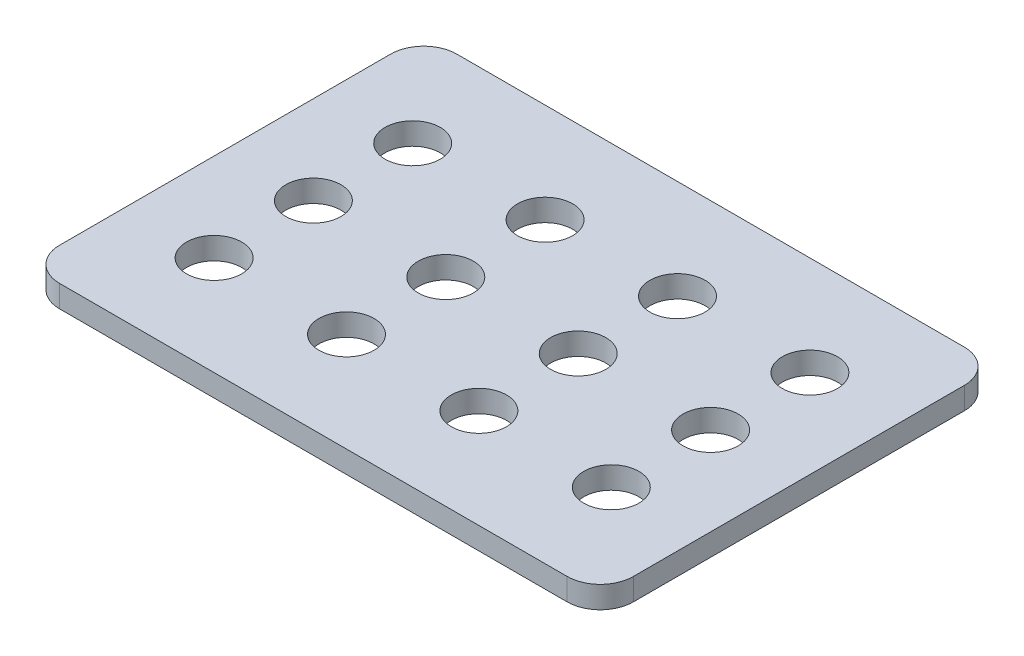
SolidWorks part; units mm, degrees
ref_plane "Front Plane" through (0, 0, 0) normal (0, 0, 1) x (1, 0, 0)
ref_plane "Top Plane" through (0, 0, 0) normal (0, 1, 0) x (1, 0, 0)
ref_plane "Right Plane" through (0, 0, 0) normal (1, 0, 0) x (0, 0, -1)
sketch "Sketch1" plane through (0, 0, 0) normal (0, 1, 0) x (1, 0, 0)
  line L0 (40, 45) -> (0, 45) construction
  line L1 (15, 0) -> (245, 0)
  line L2 (0, 15) -> (0, 165)
  line L3 (15, 180) -> (245, 180)
  line L4 (260, 15) -> (260, 165)
  line L5 (220, 45) -> (260, 45) construction
  arc A0 (15, 0) -> (0, 15) centre (15, 15) cw
  arc A1 (245, 0) -> (260, 15) centre (245, 15) ccw
  arc A2 (260, 165) -> (245, 180) centre (245, 165) ccw
  arc A3 (0, 165) -> (15, 180) centre (15, 165) cw
  circle A4 centre (40, 45) radius 12.5
  circle A5 centre (40, 90) radius 12.5
  circle A6 centre (40, 135) radius 12.5
  circle A7 centre (100, 45) radius 12.5
  circle A8 centre (100, 90) radius 12.5
  circle A9 centre (100, 135) radius 12.5
  circle A10 centre (160, 45) radius 12.5
  circle A11 centre (160, 90) radius 12.5
  circle A12 centre (160, 135) radius 12.5
  circle A13 centre (220, 45) radius 12.5
  circle A14 centre (220, 90) radius 12.5
  circle A15 centre (220, 135) radius 12.5
  point P7 (0, 0)
  point P10 (260, 0)
  point P13 (260, 180)
  dimension "D3" = 15
  dimension "D4" = 25
  dimension "D1" = 260
  dimension "D2" = 180
  dimension "D5" = 45
  dimension "D6" = 45
  dimension "D7" = 45
  dimension "D8" = 4
extrude "Boss-Extrude1" add sketch "Sketch1" against normal blind 10
